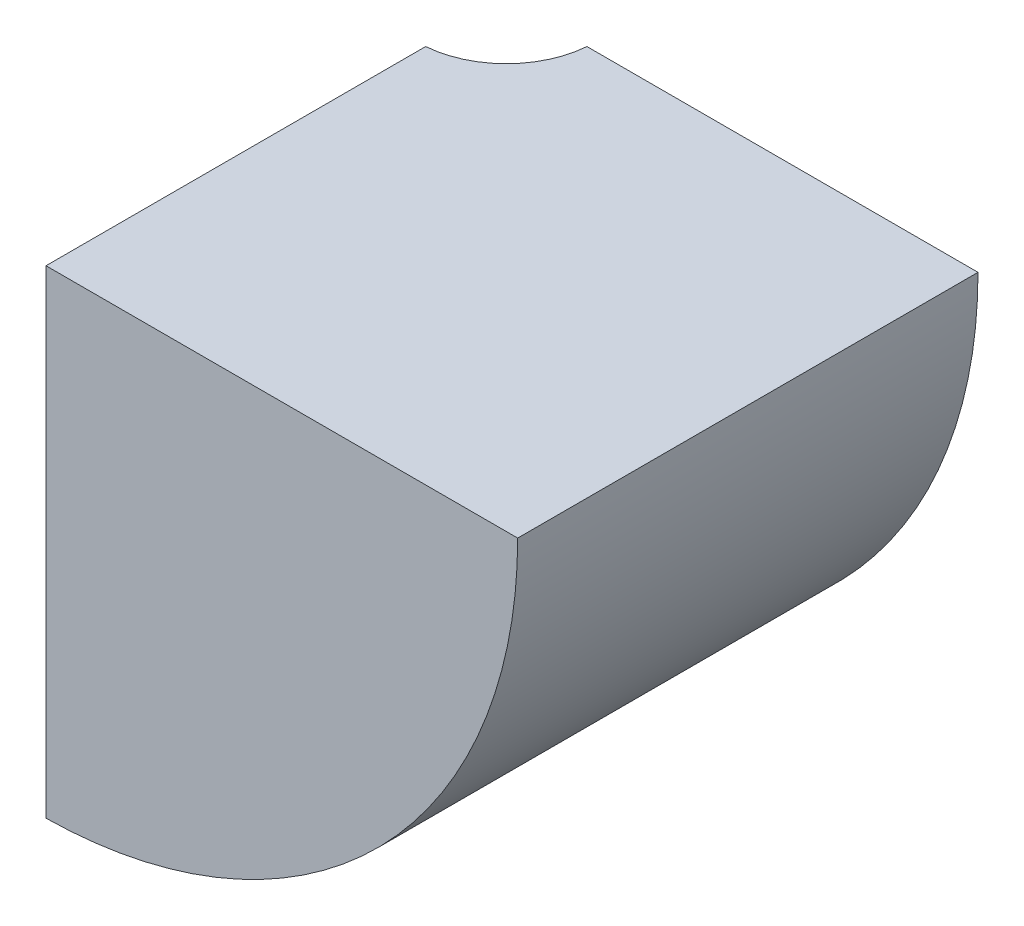
SolidWorks part; units mm, degrees
ref_plane "Front Plane" through (0, 0, 0) normal (0, 0, 1) x (1, 0, 0)
ref_plane "Top Plane" through (0, 0, 0) normal (0, 1, 0) x (1, 0, 0)
ref_plane "Right Plane" through (0, 0, 0) normal (1, 0, 0) x (0, 0, -1)
sketch "Sketch1" plane through (0, 0, 0) normal (0, 0, 1) x (1, 0, 0)
  circle A0 centre (0, 0) radius 42
  dimension "D1" = 84
extrude "Boss-Extrude1" add sketch "Sketch1" along normal blind 41
sketch "Sketch2" plane through (0, 0, 41) normal (0, 0, 1) x (1, 0, 0)
  line L0 (0, 0) -> (42, 0)
  line L1 (0, 0) -> (0, -42)
  circle A0 centre (0, 0) radius 42 construction
  arc A1 (42, 0) -> (0, -42) centre (0, 0) ccw
extrude "Cut-Extrude1" cut sketch "Sketch2" against normal through all
sketch "Sketch3" plane through (0, 0, 0) normal (0, 1, 0) x (1, 0, 0)
  circle A0 centre (0, 0) radius 7.7
  dimension "D1" = 15.4
extrude "Cut-Extrude2" cut sketch "Sketch3" against normal through all
sketch "Sketch4" plane through (0, 0, 0) normal (0, 1, 0) x (1, 0, 0)
  line L1 (0, -41) -> (0.6, -41)
  line L2 (0, -41) -> (0, -6.788)
  line L3 (0, -6.788) -> (0.6, -6.788)
  line L4 (0.6, -41) -> (0.6, -6.788)
  line L5 (42, 0) -> (6.2585, 0)
  line L6 (42, 0) -> (42, -0.6)
  line L7 (42, -0.6) -> (6.2585, -0.6)
  line L8 (6.2585, 0) -> (6.2585, -0.6)
  dimension "D1" = 0.6
  dimension "D2" = 0.6
extrude "Cut-Extrude3" cut sketch "Sketch4" against normal through all
